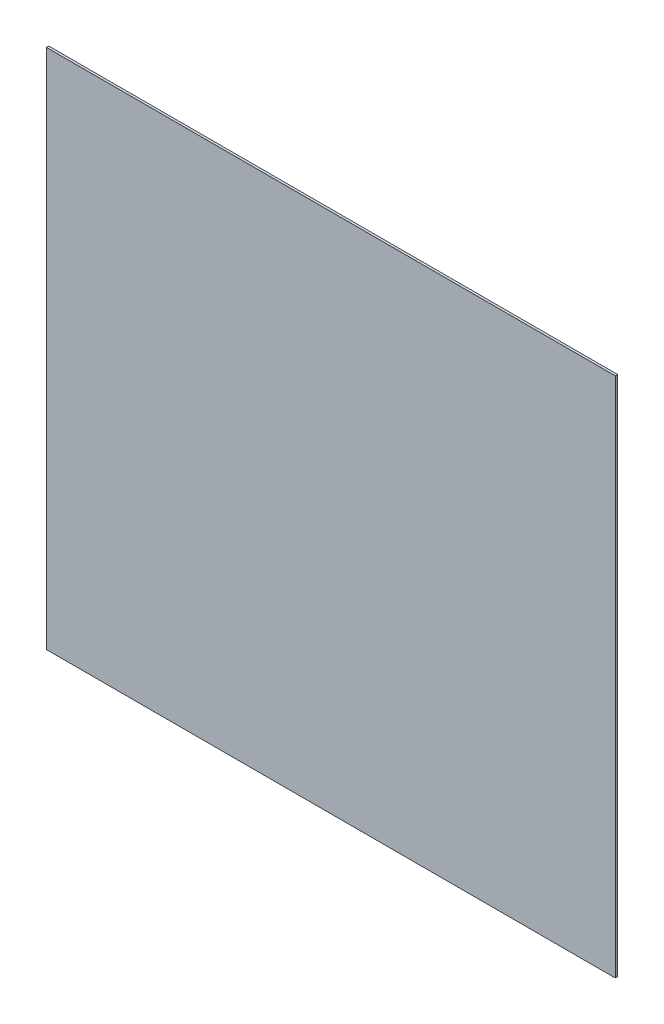
SolidWorks part; units mm, degrees
ref_plane "정면" through (0, 0, 0) normal (0, 0, 1) x (1, 0, 0)
ref_plane "윗면" through (0, 0, 0) normal (0, 1, 0) x (1, 0, 0)
ref_plane "우측면" through (0, 0, 0) normal (1, 0, 0) x (0, 0, -1)
sketch "스케치1" plane through (0, 0, 0) normal (0, 0, 1) x (1, 0, 0)
  line L1 (0, 0) -> (48, 0)
  line L2 (0, 0) -> (0, 44)
  line L3 (0, 44) -> (48, 44)
  line L4 (48, 0) -> (48, 44)
  dimension "D1" = 48
  dimension "D2" = 44
extrude "보스-돌출1" add sketch "스케치1" along normal blind 0.2
